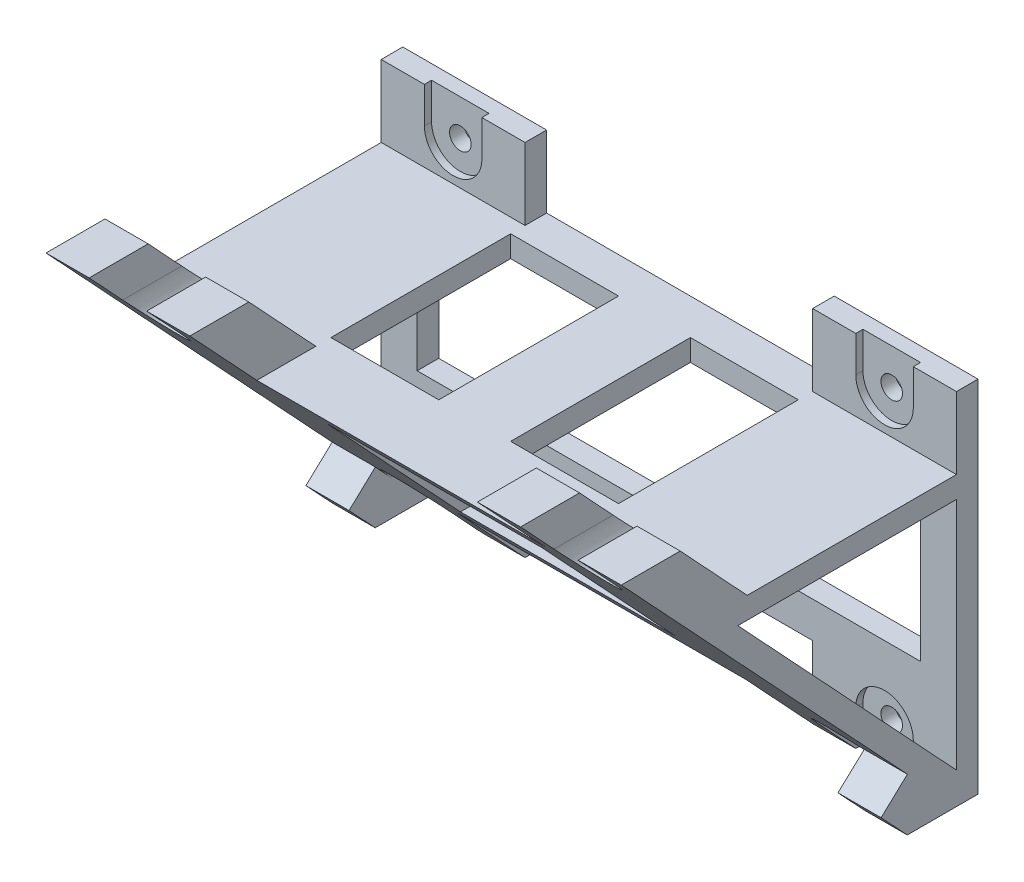
SolidWorks part; units mm, degrees
ref_plane "前视基准面" through (0, 0, 0) normal (0, 0, 1) x (1, 0, 0)
ref_plane "上视基准面" through (0, 0, 0) normal (0, 1, 0) x (1, 0, 0)
ref_plane "右视基准面" through (0, 0, 0) normal (1, 0, 0) x (0, 0, -1)
sketch "草图1" plane through (0, 0, 0) normal (0, 0, 1) x (1, 0, 0)
  line L0 (0, 0) -> (0, 50)
  line L1 (20, 50) -> (20, 40)
  line L2 (60, 40) -> (20, 40)
  line L3 (60, 50) -> (60, 40)
  line L4 (20, 50) -> (0, 50)
  line L5 (60, 50) -> (80, 50)
  line L6 (80, 50) -> (80, 0)
  line L7 (80, 0) -> (60, 0)
  line L8 (60, 0) -> (60, 10)
  line L9 (60, 10) -> (20, 10)
  line L10 (20, 10) -> (20, 0)
  line L11 (20, 0) -> (0, 0)
  point P13 (0, 0)
  point P14 (0, 0)
  dimension "D1" = 50
  dimension "D2" = 20
  dimension "D3" = 40
  dimension "D4" = 20
  dimension "D5" = 20
  dimension "D6" = 40
  dimension "D7" = 20
  dimension "D8" = 10
  dimension "D10" = 10
extrude "凸台-拉伸2" add sketch "草图1" along normal blind 2
sketch "草图3" plane through (0, 0, 2) normal (0, 0, 1) x (1, 0, 0)
  line L0 (10, 5) -> (10, 0) construction
  line L2 (20, 0) -> (0, 0) construction
  line L3 (10, 50) -> (10, 45) construction
  line L4 (20, 50) -> (0, 50) construction
  line L5 (70, 50) -> (70, 45) construction
  line L6 (60, 50) -> (80, 50) construction
  line L7 (70, 0) -> (70, 5) construction
  line L8 (80, 0) -> (60, 0) construction
  circle A1 centre (10, 45) radius 1.5
  circle A2 centre (10, 5) radius 1.5
  circle A3 centre (70, 45) radius 1.5
  circle A4 centre (70, 5) radius 1.5
  point P20 (0, 0)
  dimension "D1" = 3
  dimension "D4" = 3
  dimension "D5" = 3
  dimension "D6" = 3
  dimension "D2" = 40
  dimension "D3" = 40
  dimension "D7" = 60
  dimension "D8" = 60
  dimension "D9" = 10
  dimension "D10" = 10
  dimension "D11" = 10
  dimension "D12" = 10
extrude "切除-拉伸1" cut sketch "草图3" against normal through all
sketch "草图5" plane through (0, 0, 2) normal (0, 0, 1) x (1, 0, 0)
  line L0 (0, 50) -> (6, 50)
  line L1 (20, 50) -> (0, 50) construction
  line L2 (6, 50) -> (6, 45)
  line L3 (14, 45) -> (14, 50)
  line L4 (14, 50) -> (20, 50)
  line L5 (20, 50) -> (20, 40)
  line L6 (20, 40) -> (60, 40)
  line L7 (60, 40) -> (60, 50)
  line L8 (60, 50) -> (66, 50)
  line L9 (60, 50) -> (80, 50) construction
  line L10 (66, 50) -> (66, 45)
  line L11 (74, 45) -> (74, 50)
  line L12 (74, 50) -> (80, 50)
  line L13 (80, 50) -> (80, 0)
  line L14 (80, 0) -> (74, 0)
  line L15 (80, 0) -> (60, 0) construction
  line L16 (74, 0) -> (74, 5)
  line L17 (66, 5) -> (66, 0)
  line L18 (66, 0) -> (60, 0)
  line L19 (60, 0) -> (60, 10)
  line L20 (60, 10) -> (20, 10)
  line L21 (20, 10) -> (20, 0)
  line L22 (20, 0) -> (14, 0)
  line L23 (20, 0) -> (0, 0) construction
  line L24 (14, 0) -> (14, 5)
  line L25 (6, 5) -> (6, 0)
  line L26 (6, 0) -> (0, 0)
  line L27 (0, 0) -> (0, 50)
  arc A0 (6, 45) -> (14, 45) centre (10, 45) ccw
  arc A1 (66, 45) -> (74, 45) centre (70, 45) ccw
  arc A2 (74, 5) -> (66, 5) centre (70, 5) ccw
  arc A3 (14, 5) -> (6, 5) centre (10, 5) ccw
  dimension "D5" = 4
  dimension "D6" = 4
  dimension "D7" = 4
  dimension "D8" = 4
  dimension "D1" = 5
  dimension "D2" = 5
  dimension "D3" = 5
  dimension "D4" = 5
  dimension "D9" = 10
  dimension "D10" = 10
  dimension "D11" = 10
  dimension "D12" = 10
extrude "凸台-拉伸3" add sketch "草图5" along normal blind 1
draft "拔模4" type of draft neutral plane draft angle 43 faces to draft 1 face at (40, 25, 3) neutral plane through (20, 0, 2) neutral plane normal (0, -1, 0) parameters "D1"=43
sketch "草图6" plane through (0, -1.4963, 1.6046) normal (0, -0.682, 0.7314) x (1, 0, 0)
  line L0 (6, 2.046) -> (6, 12.046)
  line L1 (6, 2.046) -> (6, 8.8826) construction
  line L2 (6, 12.046) -> (0, 12.046)
  line L3 (0, 70.4124) -> (0, 2.046) construction
  line L4 (0, 12.046) -> (0, 2.046)
  line L5 (0, 2.046) -> (6, 2.046)
  dimension "D1" = 10
  dimension "D2" = 6
extrude "凸台-拉伸4" add sketch "草图6" along normal blind 5
sketch "草图7" plane through (0, -1.4963, 1.6046) normal (0, -0.682, 0.7314) x (1, 0, 0)
  line L0 (74, 2.046) -> (80, 2.046)
  line L1 (80, 2.046) -> (80, 12.046)
  line L2 (80, 2.046) -> (80, 70.4124) construction
  line L3 (80, 12.046) -> (74, 12.046)
  line L4 (74, 12.046) -> (74, 2.046)
  dimension "D1" = 10
  dimension "D2" = 6
extrude "凸台-拉伸5" add sketch "草图7" along normal blind 5 contours L4 L0 L1 L3
sketch "草图8" plane through (80, 0, 0) normal (1, 0, 0) x (0, 0, -1)
  line L0 (-3, 0) -> (-9.8366, 0)
  line L1 (-6.6568, -3.41) -> (-13.4768, 3.9035) construction
  line L2 (-9.8366, 0) -> (-6.6568, -3.41)
  line L3 (-6.6568, -3.41) -> (-3, 0)
extrude "切除-拉伸2" cut sketch "草图8" against normal through all
sketch "草图11" plane through (80, 0, 0) normal (1, 0, 0) x (0, 0, -1)
  line L0 (-3, 37) -> (-3, 13)
  line L1 (-3, 13) -> (-11.0207, 13)
  line L2 (-11.0207, 13) -> (-33.4011, 37)
  line L3 (-33.4011, 37) -> (-3, 37)
  line L4 (0, 50) -> (0, 0) construction
  line L6 (-49.6258, 50) -> (0, 50) construction
  line L7 (-9.8366, 0) -> (0, 0) construction
  line L9 (-9.82, 7.3135) -> (-49.6258, 50) construction
  dimension "D1" = 3
  dimension "D2" = 13
  dimension "D3" = 13
  dimension "D4" = 3
  dimension "D5" = 3
extrude "切除-拉伸4" cut sketch "草图11" against normal through all contours L3 L0 L1 L2
sketch "草图12" plane through (80, 0, 0) normal (1, 0, 0) x (0, 0, -1)
  line L0 (-3, 50) -> (-41.4218, 50)
  line L1 (-49.6258, 50) -> (0, 50) construction
  line L2 (-41.4218, 50) -> (-32.0966, 40)
  line L3 (-32.0966, 40) -> (-3, 40)
  line L4 (-3, 40) -> (-3, 50)
  line L5 (0, 50) -> (0, 0) construction
  line L6 (-9.82, 7.3135) -> (-49.6258, 50) construction
  point P10 (0, 0)
  point P11 (0, 0)
  point P12 (-38.558, 38.1313)
  dimension "D1" = 3
  dimension "D2" = 10
  dimension "D3" = 3
  dimension "D4" = 6
  dimension "D5" = 6
  dimension "D6" = 0
extrude "切除-拉伸5" cut sketch "草图12" against normal through all
sketch "草图14" plane through (80, 0, 0) normal (1, 0, 0) x (0, 0, -1)
  line L0 (-11.0207, 13) -> (-3, 4.3988)
  line L1 (-3, 4.3988) -> (-3, 13)
  line L2 (-3, 13) -> (-11.0207, 13)
  dimension "D1" = 43
extrude "切除-拉伸6" cut sketch "草图14" against normal through all contours L2 L0 L1
sketch "草图15" plane through (0, 0, 0) normal (0, 0, -1) x (-1, 0, 0)
  line L0 (-25, 15) -> (-55, 15)
  line L1 (-55, 15) -> (-55, 35)
  line L2 (-55, 35) -> (-25, 35)
  line L3 (-25, 35) -> (-25, 15)
  line L4 (-60, 10) -> (-20, 10) construction
  line L5 (-60, 40) -> (-20, 40) construction
  line L6 (-20, 10) -> (-20, 40) construction
  line L7 (-60, 10) -> (-60, 40) construction
  dimension "D1" = 20
  dimension "D2" = 30
  dimension "D3" = 5
  dimension "D4" = 5
  dimension "D5" = 5
  dimension "D6" = 5
extrude "切除-拉伸7" cut sketch "草图15" against normal through all
sketch "草图16" plane through (0, 0, 0) normal (0, 0, -1) x (-1, 0, 0)
  line L0 (-25, 15) -> (-5, 15)
  line L1 (-5, 15) -> (-5, 35)
  line L2 (-5, 35) -> (-25, 35)
  line L3 (-25, 35) -> (-25, 15)
  line L4 (-55, 35) -> (-55, 15)
  line L5 (-55, 15) -> (-75, 15)
  line L6 (-75, 15) -> (-75, 35)
  line L7 (-75, 35) -> (-55, 35)
  line L8 (0, 0) -> (0, 50) construction
  line L9 (-80, 50) -> (-80, 0) construction
  dimension "D1" = 5
  dimension "D2" = 5
extrude "切除-拉伸8" cut sketch "草图16" against normal blind 5
sketch "草图17" plane through (0, 40, 0) normal (0, 1, 0) x (1, 0, 0)
  line L0 (60, -30) -> (60, -5)
  line L1 (60, -5) -> (45, -5)
  line L2 (45, -5) -> (45, -30)
  line L3 (45, -30) -> (60, -30)
  line L4 (35, -5) -> (20, -5)
  line L5 (20, -5) -> (20, -30)
  line L6 (20, -30) -> (35, -30)
  line L7 (35, -30) -> (35, -5)
  line L8 (80, -32.0966) -> (80, -3) construction
  line L9 (0, -32.0966) -> (0, -3) construction
  line L10 (60, 0) -> (20, 0) construction
  dimension "D1" = 15
  dimension "D2" = 15
  dimension "D3" = 20
  dimension "D4" = 20
  dimension "D5" = 5
  dimension "D6" = 5
  dimension "D7" = 25
extrude "切除-拉伸9" cut sketch "草图17" against normal blind 5
